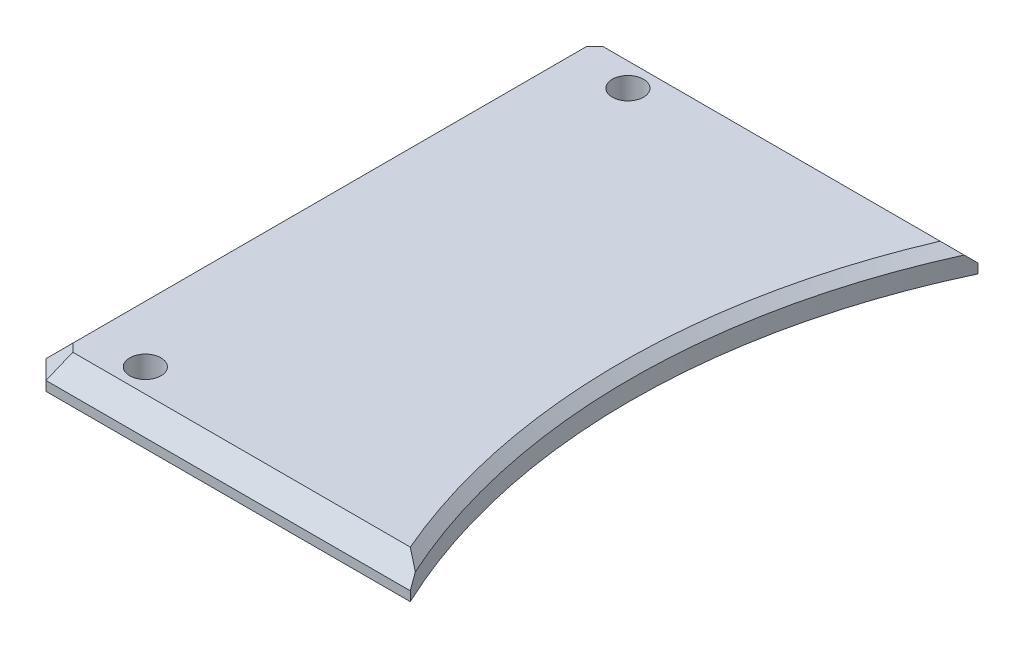
SolidWorks part; units mm, degrees
ref_plane "Plan de face" through (0, 0, 0) normal (0, 0, 1) x (1, 0, 0)
ref_plane "Plan de dessus" through (0, 0, 0) normal (0, 1, 0) x (1, 0, 0)
ref_plane "Plan de droite" through (0, 0, 0) normal (1, 0, 0) x (0, 0, -1)
sketch "Esquisse1" plane through (0, 0, 0) normal (0, 1, 0) x (1, 0, 0)
  line L1 (-20.25, -30) -> (20.25, -30)
  line L2 (-20.25, -30) -> (-20.25, 30)
  line L3 (-20.25, 30) -> (20.25, 30)
  line L5 (-20.25, -30) -> (20.25, 30) construction
  line L6 (-20.25, 30) -> (20.25, -30) construction
  arc A0 (20.25, 30) -> (20.25, -30) centre (83.4956, 0) ccw
  circle A1 centre (-12.25, -25.5) radius 1.65
  circle A3 centre (-12.25, 25.5) radius 1.65
  point P0 (0, 0)
  dimension "D3" = 70
  dimension "D4" = 83.4956
  dimension "D5" = 3.3
  dimension "D7" = 3.3
  dimension "D1" = 40.5
  dimension "D2" = 60
  dimension "D9" = 4.5
  dimension "D11" = 4.5
  dimension "D13" = 8
  dimension "D15" = 8
extrude "Boss.-Extru.1" add sketch "Esquisse1" against normal blind 3
chamfer "Chanfrein1" distance 2 angle 45 2 edges at (-20.25, -1.5, 30) (-20.25, -1.5, -30)
chamfer "Chanfrein3" distance 2 angle 45 5 edges at (1, 0, -30) (-19.25, 0, -29) (1, 0, 30) (-19.25, 0, 29) (-20.25, 0, 0)
chamfer "Chanfrein4" distance 1 angle 45 1 edges at (13.4956, 0, 0)
